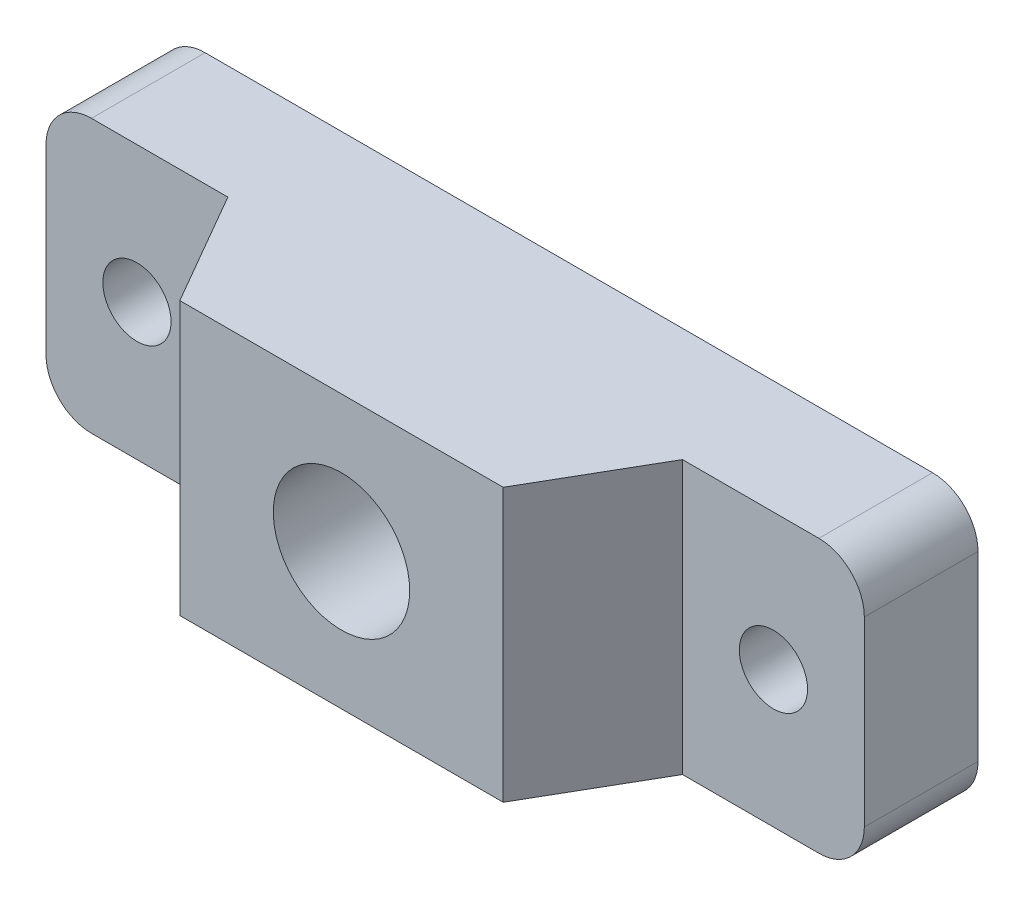
SolidWorks part; units mm, degrees
ref_plane "Plan de face" through (0, 0, 0) normal (0, 0, 1) x (1, 0, 0)
ref_plane "Plan de dessus" through (0, 0, 0) normal (0, 1, 0) x (1, 0, 0)
ref_plane "Plan de droite" through (0, 0, 0) normal (1, 0, 0) x (0, 0, -1)
sketch "Esquisse1" plane through (0, 0, 0) normal (0, 0, 1) x (1, 0, 0)
  line L1 (18, 6) -> (-18, 6)
  line L2 (18, 6) -> (18, -6)
  line L3 (18, -6) -> (-18, -6)
  line L4 (-18, 6) -> (-18, -6)
  line L5 (18, 6) -> (-18, -6) construction
  line L6 (18, -6) -> (-18, 6) construction
  circle A0 centre (0, 0) radius 3
  dimension "D1" = 6
  dimension "D2" = 12
  dimension "D3" = 36
extrude "Boss.-Extru.1" add sketch "Esquisse1" along normal blind 10
sketch "Esquisse2" plane through (0, 0, 10) normal (0, 0, 1) x (1, 0, 0)
  line L0 (-18, 0) -> (18, 0) construction
  line L1 (-18, 6) -> (-18, -6) construction
  line L2 (18, -6) -> (18, 6) construction
  circle A0 centre (-14, 0) radius 1.5
  circle A1 centre (14, 0) radius 1.5
  dimension "D1" = 3
  dimension "D2" = 3
  dimension "D3" = 4
  dimension "D4" = 4
extrude "Enlèv. mat.-Extru.1" cut sketch "Esquisse2" against normal through all
sketch "Esquisse3" plane through (0, -6, 0) normal (0, -1, 0) x (1, 0, 0)
  line L0 (-18, 0) -> (-18, 5)
  line L1 (-18, 10) -> (-18, 0) construction
  line L2 (-18, 5) -> (-10, 5)
  line L3 (-10, 5) -> (-7.1132, 10)
  line L4 (-18, 10) -> (18, 10) construction
  line L5 (-7.1132, 10) -> (7.1132, 10)
  line L6 (7.1132, 10) -> (10, 5)
  line L7 (10, 5) -> (18, 5)
  line L8 (18, 10) -> (18, 0) construction
  line L9 (18, 5) -> (18, 0)
  line L10 (18, 0) -> (-18, 0)
  dimension "D1" = 8
  dimension "D2" = 8
  dimension "D3" = 60
  dimension "D4" = 60
extrude "Enlèv. mat.-Extru.2" cut sketch "Esquisse3" against normal through all flip side to cut
fillet "Congé1" radius 2 4 edges at (-18, -6, 2.5) (-18, 6, 2.5) (18, 6, 2.5) (18, -6, 2.5)
